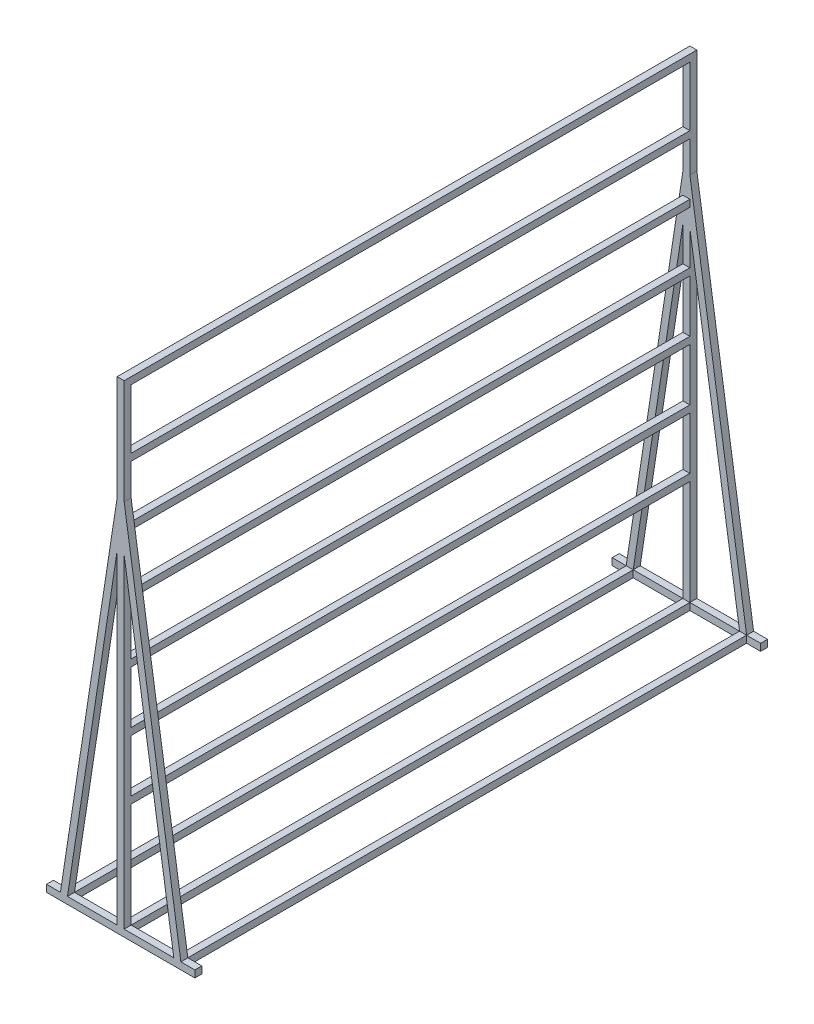
SolidWorks part; units mm, degrees
ref_plane "Alzado" through (0, 0, 0) normal (0, 0, 1) x (1, 0, 0)
ref_plane "Planta" through (0, 0, 0) normal (0, 1, 0) x (1, 0, 0)
ref_plane "Vista lateral" through (0, 0, 0) normal (1, 0, 0) x (0, 0, -1)
sketch "Croquis1" plane through (0, 0, 0) normal (1, 0, 0) x (0, 0, -1)
  line L1 (20, -20) -> (-20, -20)
  line L2 (20, -20) -> (20, 20)
  line L3 (20, 20) -> (-20, 20)
  line L4 (-20, -20) -> (-20, 20)
  line L5 (20, -20) -> (-20, 20) construction
  line L6 (20, 20) -> (-20, -20) construction
  point P0 (0, 0)
  dimension "D1" = 40
extrude "Extruir1" add sketch "Croquis1" along normal mid plane 850
sketch "Croquis2" plane through (0, 0, -20) normal (0, 0, -1) x (-1, 0, 0)
  line L0 (-425, 20) -> (425, 20) construction
  line L1 (-20, -20) -> (20, -20)
  line L2 (-20, -20) -> (-20, 20)
  line L3 (-20, 20) -> (20, 20)
  line L4 (20, -20) -> (20, 20)
  line L5 (-20, -20) -> (20, 20) construction
  line L6 (-20, 20) -> (20, -20) construction
  line L7 (425, 20) -> (425, -20) construction
  point P0 (0, 0)
extrude "Extruir2" add sketch "Croquis2" along normal blind 1600
ref_plane "Plano1" through (0, 0, -1620) normal (0, 0, -1) x (-1, 0, 0)
mirror "Simetría1" about plane through (-20, 20, -1620) normal (0, 0, 1) of bodies 102
sketch "Croquis3" plane through (0, 20, 0) normal (0, 1, 0) x (1, 0, 0)
  line L0 (-20, 1620) -> (20, 1620) construction
  line L1 (20, -20) -> (-20, -20)
  line L2 (20, -20) -> (20, 20)
  line L3 (20, 20) -> (-20, 20)
  line L4 (-20, -20) -> (-20, 20)
  line L5 (20, -20) -> (-20, 20) construction
  line L6 (20, 20) -> (-20, -20) construction
  line L7 (-20, 3220) -> (-20, 20) construction
  line L8 (144.7328, 1620) -> (-144.7328, 1620) construction
  line L9 (20, 3220) -> (-20, 3260) construction
  line L10 (20, 3260) -> (-20, 3220) construction
  line L11 (-20, 3260) -> (-20, 3220)
  line L12 (20, 3220) -> (-20, 3220)
  line L13 (20, 3260) -> (20, 3220)
  line L14 (20, 3260) -> (-20, 3260)
  point P0 (0, 0)
  point P17 (0, 3240)
extrude "Extruir3" add sketch "Croquis3" along normal blind 2720
sketch "Croquis4" plane through (0, 0, 20) normal (0, 0, 1) x (1, 0, 0)
  line L0 (345, 20) -> (20, 2140)
  line L1 (425, 20) -> (20, 20) construction
  line L2 (20, 2740) -> (20, 20) construction
  line L3 (304.5327, 20) -> (20, 1876.0287)
  line L4 (20, 2140) -> (20, 1876.0287)
  line L5 (304.5327, 20) -> (345, 20)
  dimension "D1" = 40
  dimension "D2" = 80
  dimension "D3" = 600
extrude "Extruir4" add sketch "Croquis4" against normal blind 40 separate body contours L0 L4 L3 L5
mirror "Simetría2" about plane through (0, 0, 0) normal (1, 0, 0) of bodies 105
mirror "Simetría3" about plane through (0, 0, -1620) normal (0, 0, -1) of bodies 106 105
sketch "Croquis5" plane through (0, 0, -20) normal (0, 0, -1) x (-1, 0, 0)
  line L0 (20, 2740) -> (20, 20) construction
  line L1 (20, 620) -> (-20, 620)
  line L2 (20, 620) -> (20, 660)
  line L3 (20, 660) -> (-20, 660)
  line L4 (-20, 620) -> (-20, 660)
  line L5 (-20, 2740) -> (-20, 20) construction
  line L6 (425, 20) -> (425, -20) construction
  line L7 (-425, 20) -> (-20, 20) construction
  line L8 (-20, 2740) -> (-20, 20) construction
  line L9 (-20, 960) -> (20, 960)
  line L10 (-20, 960) -> (-20, 1000)
  line L11 (-20, 1000) -> (20, 1000)
  line L12 (20, 960) -> (20, 1000)
  line L13 (20, 2740) -> (20, 20) construction
  line L14 (-20, 660) -> (-20, 960) construction
  line L15 (-20, 1300) -> (20, 1300)
  line L16 (-20, 1300) -> (-20, 1340)
  line L17 (-20, 1340) -> (20, 1340)
  line L18 (20, 1300) -> (20, 1340)
  line L19 (-20, 1000) -> (-20, 1300) construction
  line L20 (-20, 1340) -> (-20, 1640) construction
  line L21 (-20, 1640) -> (20, 1640)
  line L22 (-20, 1640) -> (-20, 1680)
  line L23 (-20, 1680) -> (20, 1680)
  line L24 (20, 1640) -> (20, 1680)
  line L25 (-20, 1680) -> (-20, 1980) construction
  line L26 (-20, 1980) -> (20, 1980)
  line L27 (-20, 1980) -> (-20, 2020)
  line L28 (-20, 2020) -> (20, 2020)
  line L29 (20, 1980) -> (20, 2020)
  line L30 (-20, 2020) -> (-20, 2320) construction
  line L31 (-20, 2320) -> (20, 2320)
  line L32 (-20, 2320) -> (-20, 2360)
  line L33 (-20, 2360) -> (20, 2360)
  line L34 (20, 2320) -> (20, 2360)
  line L36 (-20, 2740) -> (20, 2740)
  line L37 (-20, 2740) -> (-20, 2700)
  line L38 (-20, 2700) -> (20, 2700)
  line L39 (20, 2740) -> (20, 2700)
  dimension "D1" = 600
  dimension "D2" = 300
extrude "Extruir5" add sketch "Croquis5" along normal up to surface (3200 mm away) up to face at (-5, 2060, -3220)
sketch "Croquis6" plane through (0, 0, -20) normal (0, 0, -1) x (-1, 0, 0)
  line L0 (-425, -20) -> (425, -20) construction
  line L1 (-304.5327, 20) -> (-344.5327, 20)
  line L2 (-304.5327, 20) -> (-304.5327, -20)
  line L3 (-304.5327, -20) -> (-344.5327, -20)
  line L4 (-344.5327, 20) -> (-344.5327, -20)
  line L5 (-425, 20) -> (-425, -20) construction
  line L6 (0, 0) -> (0, -331.506) construction
  line L7 (344.5327, 20) -> (344.5327, -20)
  line L8 (304.5327, -20) -> (344.5327, -20)
  line L9 (304.5327, 20) -> (304.5327, -20)
  line L10 (304.5327, 20) -> (344.5327, 20)
extrude "Extruir6" add sketch "Croquis6" along normal up to surface (3200 mm away) up to face at (0, 2000, -3220)
